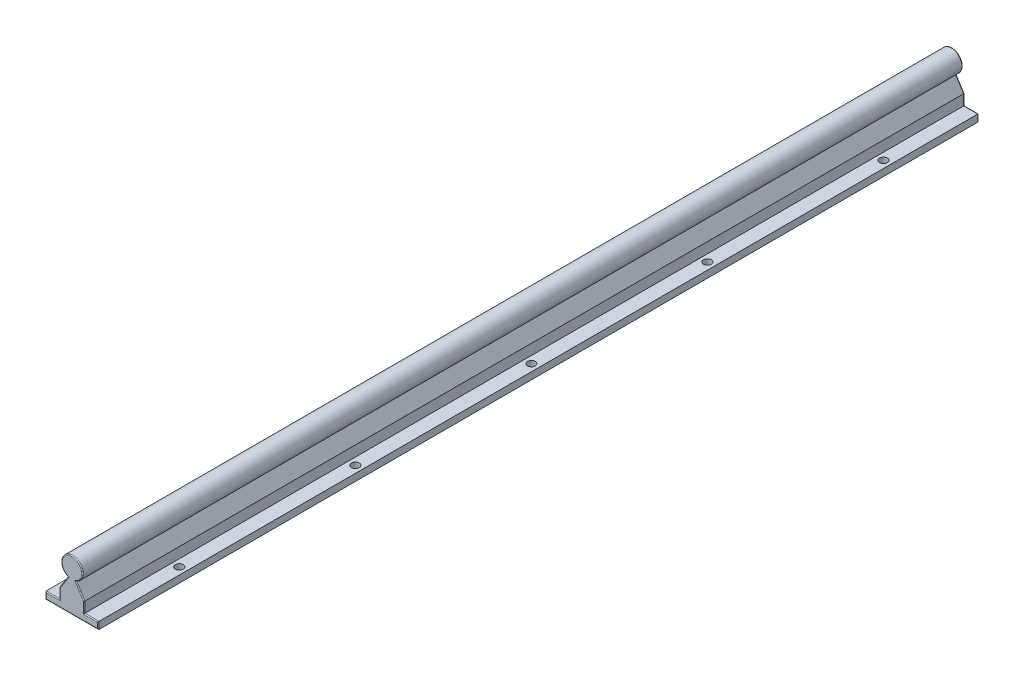
SolidWorks part; units mm, degrees
ref_plane "Front Plane" through (0, 0, 0) normal (0, 0, 1) x (1, 0, 0)
ref_plane "Top Plane" through (0, 0, 0) normal (0, 1, 0) x (1, 0, 0)
ref_plane "Right Plane" through (0, 0, 0) normal (1, 0, 0) x (0, 0, -1)
sketch "Sketch1" plane through (0, 0, 0) normal (0, 0, 1) x (1, 0, 0)
  line L0 (-15, 0) -> (15, 0)
  line L1 (15, 0) -> (15, 4)
  line L3 (-15, 4) -> (-15, 0)
  line L4 (-15, 4) -> (-7, 4)
  line L5 (7, 4) -> (7, 10)
  line L6 (7, 4) -> (15, 4)
  line L7 (-7, 10) -> (-2.2592, 17.4416)
  line L8 (2.2592, 17.4416) -> (7, 10)
  line L14 (-7, 4) -> (-7, 10)
  arc A0 (2.2592, 17.4416) -> (-2.2592, 17.4416) centre (0, 23) ccw
  point P4 (0, 0)
  dimension "D8" = 12
  dimension "D1" = 30
  dimension "D2" = 4
  dimension "D3" = 8
  dimension "D4" = 6
  dimension "D6" = 65
  dimension "D10" = 8
  dimension "D11" = 6
extrude "Boss-Extrude1" add sketch "Sketch1" along normal blind 500 contours L7 A0 L8 L5 L6 L1 L0 L3 L4 L14
sketch "Sketch2" plane through (0, 0, 0) normal (0, -1, 0) x (1, 0, 0)
  line L0 (-11, 0) -> (-11, 50) construction
  line L1 (-15, 0) -> (15, 0) construction
  line L2 (-15, 500) -> (-15, 0) construction
  circle A0 centre (-11, 50) radius 2.25
  dimension "D3" = 4.5
  dimension "D1" = 4
  dimension "D2" = 50
extrude "Cut-Extrude1" cut sketch "Sketch2" against normal through all
pattern_linear "LPattern1" count 5 spacing 100 along (0, 0, 1) count 2 spacing 22 along (1, 0, 0) of "Cut-Extrude1"
fillet "Fillet1" radius 0.5 20 edges at (-4.6296, 13.7208, 500) (0, 29, 500) (4.6296, 13.7208, 500) (7, 7, 500) (11, 4, 500) (15, 2, 500) (0, 0, 500) (-15, 2, 500) (-11, 4, 500) (-7, 7, 500) (-11, 4, 0) (-15, 2, 0) (0, 0, 0) (15, 2, 0) (11, 4, 0) (7, 7, 0) (4.6296, 13.7208, 0) (0, 29, 0) (-4.6296, 13.7208, 0) (-7, 7, 0)
